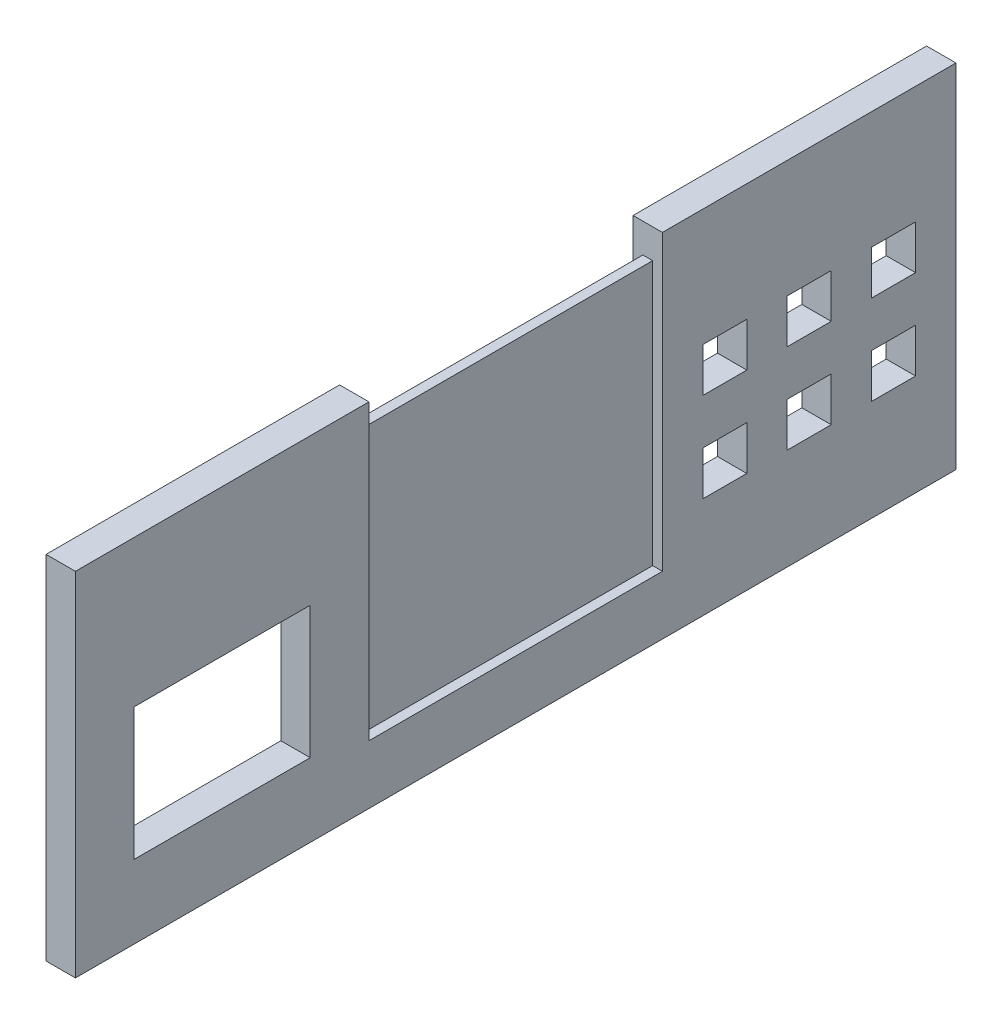
SolidWorks part; units mm, degrees
ref_plane "Front Plane" through (0, 0, 0) normal (0, 0, 1) x (1, 0, 0)
ref_plane "Top Plane" through (0, 0, 0) normal (0, 1, 0) x (1, 0, 0)
ref_plane "Right Plane" through (0, 0, 0) normal (1, 0, 0) x (0, 0, -1)
sketch "Sketch1" plane through (0, 0, 0) normal (1, 0, 0) x (0, 0, -1)
  line L1 (0, 0) -> (-381, 0)
  line L2 (0, 0) -> (0, 152.4)
  line L3 (0, 152.4) -> (-381, 152.4)
  line L4 (-381, 0) -> (-381, 152.4)
  dimension "D1" = 381
  dimension "D2" = 152.4
extrude "Boss-Extrude2" add sketch "Sketch1" along normal blind 12.7
sketch "Sketch2" plane through (12.7, 0, 0) normal (1, 0, 0) x (0, 0, -1)
  line L0 (-254, 152.4) -> (-254, 25.4)
  line L1 (0, 152.4) -> (-381, 152.4) construction
  line L2 (-254, 25.4) -> (-127, 25.4)
  line L3 (-127, 25.4) -> (-127, 152.4)
  line L4 (-127, 152.4) -> (-254, 152.4)
  line L5 (-381, 152.4) -> (-381, 0) construction
  dimension "D1" = 127
  dimension "D2" = 127
  dimension "D3" = 127
extrude "Cut-Extrude1" cut sketch "Sketch2" against normal blind 12.7 contours L4 L0 L2 L3
sketch "Sketch3" plane through (12.7, 0, 0) normal (1, 0, 0) x (0, 0, -1)
  line L0 (0, 152.4) -> (-127, 152.4) construction
  line L1 (-109.5375, 101.6) -> (-90.4875, 101.6)
  line L2 (-109.5375, 101.6) -> (-109.5375, 82.55)
  line L3 (-109.5375, 82.55) -> (-90.4875, 82.55)
  line L4 (-90.4875, 101.6) -> (-90.4875, 82.55)
  line L5 (-127, 25.4) -> (-127, 152.4) construction
  line L6 (-254, 152.4) -> (-254, 25.4) construction
  line L7 (-73.025, 101.6) -> (-53.975, 101.6)
  line L8 (-73.025, 101.6) -> (-73.025, 82.55)
  line L9 (-73.025, 82.55) -> (-53.975, 82.55)
  line L10 (-53.975, 101.6) -> (-53.975, 82.55)
  line L11 (-36.5125, 82.55) -> (-17.4625, 82.55)
  line L12 (-36.5125, 82.55) -> (-36.5125, 101.6)
  line L13 (-36.5125, 101.6) -> (-17.4625, 101.6)
  line L14 (-17.4625, 82.55) -> (-17.4625, 101.6)
  line L15 (-109.5375, 62.866) -> (-90.4875, 62.866)
  line L16 (-109.5375, 62.866) -> (-109.5375, 43.816)
  line L17 (-109.5375, 43.816) -> (-90.4875, 43.816)
  line L18 (-90.4875, 62.866) -> (-90.4875, 43.816)
  line L19 (-73.025, 62.866) -> (-53.975, 62.866)
  line L20 (-73.025, 62.866) -> (-73.025, 43.816)
  line L21 (-73.025, 43.816) -> (-53.975, 43.816)
  line L22 (-53.975, 62.866) -> (-53.975, 43.816)
  line L23 (-36.5125, 62.866) -> (-17.4625, 62.866)
  line L24 (-36.5125, 62.866) -> (-36.5125, 43.816)
  line L25 (-36.5125, 43.816) -> (-17.4625, 43.816)
  line L26 (-17.4625, 62.866) -> (-17.4625, 43.816)
  line L27 (-279.4, 88.9) -> (-355.6, 88.9)
  line L28 (-279.4, 88.9) -> (-279.4, 31.75)
  line L29 (-279.4, 31.75) -> (-355.6, 31.75)
  line L30 (-355.6, 88.9) -> (-355.6, 31.75)
  line L31 (-381, 152.4) -> (-381, 0) construction
  line L32 (-254, 152.4) -> (-381, 152.4) construction
  dimension "D1" = 19.05
  dimension "D2" = 19.05
  dimension "D3" = 50.8
  dimension "D4" = 17.4625
  dimension "D5" = 19.05
  dimension "D6" = 19.05
  dimension "D7" = 17.4625
  dimension "D8" = 19.05
  dimension "D9" = 17.4625
  dimension "D10" = 50.8
  dimension "D11" = 19.05
  dimension "D12" = 50.8
  dimension "D13" = 19.05
  dimension "D14" = 19.05
  dimension "D15" = 19.05
  dimension "D16" = 19.05
  dimension "D17" = 19.05
  dimension "D18" = 19.05
  dimension "D19" = 17.4625
  dimension "D20" = 17.4625
  dimension "D21" = 17.4625
  dimension "D22" = 25.4
  dimension "D23" = 25.4
  dimension "D24" = 57.15
  dimension "D25" = 63.5
extrude "Cut-Extrude2" cut sketch "Sketch3" against normal blind 12.7 contours L28 L27 L30 L29 | L2 L1 L4 L3 | L16 L15 L18 L17 | L20 L19 L22 L21 | L8 L7 L10 L9 | L12 L11 L14 L13 | L24 L23 L26 L25
sketch "Sketch4" plane through (0, 25.4, 0) normal (0, 1, 0) x (1, 0, 0)
  line L0 (4.2333, -254) -> (4.2333, -127)
  line L1 (0, -254) -> (12.7, -254) construction
  line L2 (0, -127) -> (12.7, -127) construction
  line L3 (8.4667, -254) -> (8.4667, -127)
  line L4 (0, -254) -> (0, -127) construction
  line L6 (8.4667, -254) -> (4.2333, -254)
  line L7 (4.2333, -127) -> (8.4667, -127)
  dimension "D1" = 4.2333
  dimension "D2" = 4.2333
extrude "Boss-Extrude3" add sketch "Sketch4" along normal blind 114.3
